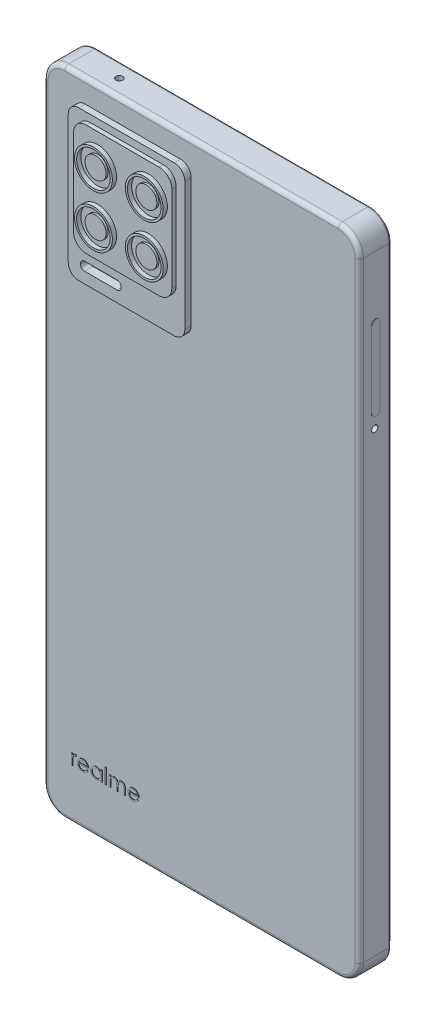
SolidWorks part; units mm, degrees
ref_plane "Front Plane" through (0, 0, 0) normal (0, 0, 1) x (1, 0, 0)
ref_plane "Top Plane" through (0, 0, 0) normal (0, 1, 0) x (1, 0, 0)
ref_plane "Right Plane" through (0, 0, 0) normal (1, 0, 0) x (0, 0, -1)
sketch "Sketch1" plane through (0, 0, 0) normal (0, 0, 1) x (1, 0, 0)
  line L1 (-14.1667, 62.0833) -> (50.8333, 62.0833)
  line L2 (-19.1667, 57.0833) -> (-19.1667, -87.9167)
  line L3 (-14.1667, -92.9167) -> (50.8333, -92.9167)
  line L4 (55.8333, 57.0833) -> (55.8333, -87.9167)
  arc A0 (50.8333, -92.9167) -> (55.8333, -87.9167) centre (50.8333, -87.9167) ccw
  arc A1 (-19.1667, -87.9167) -> (-14.1667, -92.9167) centre (-14.1667, -87.9167) ccw
  arc A2 (50.8333, 62.0833) -> (55.8333, 57.0833) centre (50.8333, 57.0833) cw
  arc A3 (-14.1667, 62.0833) -> (-19.1667, 57.0833) centre (-14.1667, 57.0833) ccw
  point P6 (55.8333, -92.9167)
  point P11 (55.8333, 62.0833)
  point P14 (-19.1667, 62.0833)
  dimension "D3" = 5
  dimension "D1" = 155
  dimension "D2" = 75
extrude "Boss-Extrude1" add sketch "Sketch1" along normal blind 7.5
sketch "Sketch2" plane through (0, 0, 7.5) normal (0, 0, 1) x (1, 0, 0)
  line L0 (-19.1667, 57.0833) -> (-19.1667, -87.9167) construction
  line L1 (-9.3422, 56.6833) -> (13.3578, 56.6833)
  line L2 (-11.8422, 54.1833) -> (-11.8422, 23.5833)
  line L3 (-9.3422, 21.0833) -> (13.3578, 21.0833)
  line L4 (15.8578, 54.1833) -> (15.8578, 23.5833)
  line L5 (50.8333, 62.0833) -> (-14.1667, 62.0833) construction
  arc A0 (-11.8422, 23.5833) -> (-9.3422, 21.0833) centre (-9.3422, 23.5833) ccw
  arc A1 (13.3578, 21.0833) -> (15.8578, 23.5833) centre (13.3578, 23.5833) ccw
  arc A2 (13.3578, 56.6833) -> (15.8578, 54.1833) centre (13.3578, 54.1833) cw
  arc A3 (-9.3422, 56.6833) -> (-11.8422, 54.1833) centre (-9.3422, 54.1833) ccw
  point P10 (-11.8422, 21.0833)
  point P13 (15.8578, 21.0833)
  point P16 (15.8578, 56.6833)
  dimension "D5" = 2.5
  dimension "D1" = 35.6
  dimension "D2" = 27.7
  dimension "D3" = 7.3244
  dimension "D4" = 5.4
extrude "Boss-Extrude3" add sketch "Sketch2" along normal blind 1.5
sketch "Sketch3" plane through (0, 0, 9) normal (0, 0, 1) x (1, 0, 0)
  line L9 (-6.5755, 55.0045) -> (10.7743, 55.0045)
  line L10 (-9.5755, 52.0045) -> (-9.5755, 31.5359)
  line L11 (-6.5755, 28.5359) -> (10.7743, 28.5359)
  line L12 (13.7743, 52.0045) -> (13.7743, 31.5359)
  arc A4 (-9.3422, 56.6833) -> (-11.8422, 54.1833) centre (-9.3422, 54.1833) ccw construction
  arc A6 (-9.5755, 31.5359) -> (-6.5755, 28.5359) centre (-6.5755, 31.5359) ccw
  arc A7 (10.7743, 28.5359) -> (13.7743, 31.5359) centre (10.7743, 31.5359) ccw
  arc A8 (10.7743, 55.0045) -> (13.7743, 52.0045) centre (10.7743, 52.0045) cw
  arc A9 (-6.5755, 55.0045) -> (-9.5755, 52.0045) centre (-6.5755, 52.0045) ccw
  dimension "D2" = 3
extrude "Boss-Extrude5" add sketch "Sketch3" along normal blind 1
sketch "Sketch4" plane through (0, 0, 9) normal (0, 0, 1) x (1, 0, 0)
  line L0 (-11.8422, 54.1833) -> (-11.8422, 23.5833) construction
  line L1 (-7.9422, 25.7817) -> (-0.2429, 25.7817)
  line L2 (-8.9422, 24.7817) -> (-8.9422, 24.7214)
  line L3 (-7.9422, 23.7214) -> (-0.2429, 23.7214)
  line L4 (0.7571, 24.7817) -> (0.7571, 24.7214)
  arc A0 (-0.2429, 25.7817) -> (0.7571, 24.7817) centre (-0.2429, 24.7817) cw
  arc A1 (-0.2429, 23.7214) -> (0.7571, 24.7214) centre (-0.2429, 24.7214) ccw
  arc A2 (-8.9422, 24.7214) -> (-7.9422, 23.7214) centre (-7.9422, 24.7214) ccw
  arc A3 (-7.9422, 25.7817) -> (-8.9422, 24.7817) centre (-7.9422, 24.7817) ccw
  dimension "D1" = 1
  dimension "D2" = 2.9
extrude "Cut-Extrude4" cut sketch "Sketch4" against normal blind 2
fillet "Fillet4" radius 1 8 edges at (-17.7022, 60.6189, 7.5) (18.3333, 62.0833, 7.5) (54.3689, 60.6189, 7.5) (55.8333, -15.4167, 7.5) (54.3689, -91.4522, 7.5) (18.3333, -92.9167, 7.5) (-17.7022, -91.4522, 7.5) (-19.1667, -15.4167, 7.5)
fillet "Fillet5" radius 0.5 8 edges at (-17.7022, 60.6189, 0) (18.3333, 62.0833, 0) (54.3689, 60.6189, 0) (55.8333, -15.4167, 0) (54.3689, -91.4522, 0) (18.3333, -92.9167, 0) (-17.7022, -91.4522, 0) (-19.1667, -15.4167, 0)
sketch "Sketch5" plane through (0, 0, 10) normal (0, 0, 1) x (1, 0, 0)
  line L0 (-3.8519, 47.8394) -> (-3.8519, 35.5813) construction
  line L1 (-3.8519, 35.5813) -> (8.2215, 35.5813) construction
  line L2 (8.2215, 35.5813) -> (8.2215, 47.8394) construction
  line L3 (8.2215, 47.8394) -> (-3.8519, 47.8394) construction
  circle A0 centre (-3.8519, 47.8394) radius 4.5
  circle A1 centre (-3.8519, 35.5813) radius 4.5
  circle A2 centre (8.2215, 35.5813) radius 4.5
  circle A3 centre (8.2215, 47.8394) radius 4.5
  circle A4 centre (-3.8519, 47.8394) radius 4
  circle A5 centre (-3.8519, 35.5813) radius 4
  circle A6 centre (8.2215, 35.5813) radius 4
  circle A7 centre (8.2215, 47.8394) radius 4
extrude "Boss-Extrude7" add sketch "Sketch5" along normal blind 1
sketch "Sketch6" plane through (0, 0, 10) normal (0, 0, 1) x (1, 0, 0)
  line L0 (-3.8519, 47.8394) -> (-3.8519, 35.5813) construction
  line L1 (-3.8519, 35.5813) -> (8.2215, 35.5813) construction
  line L2 (8.2215, 35.5813) -> (8.2215, 47.8394) construction
  line L3 (8.2215, 47.8394) -> (-3.8519, 47.8394) construction
  circle A0 centre (-3.8519, 47.8394) radius 2.5
  circle A1 centre (-3.8519, 35.5813) radius 2.5
  circle A2 centre (8.2215, 35.5813) radius 2.5
  circle A3 centre (8.2215, 47.8394) radius 2.5
extrude "Boss-Extrude8" add sketch "Sketch6" along normal blind 0.5
sketch "Sketch7" plane through (0, 0, 0) normal (0, 0, -1) x (-1, 0, 0)
  line L0 (14.1667, 61.5833) -> (-50.8333, 61.5833) construction
  line L1 (-50.8333, 60.5833) -> (14.1667, 60.5833)
  line L2 (-54.8333, 56.5833) -> (-54.8333, -87.4167)
  line L3 (-50.8333, -91.4167) -> (14.1667, -91.4167)
  line L4 (18.1667, 56.5833) -> (18.1667, -87.4167)
  line L5 (-55.3333, 57.0833) -> (-55.3333, -87.9167) construction
  arc A0 (-54.8333, -87.4167) -> (-50.8333, -91.4167) centre (-50.8333, -87.4167) ccw
  arc A1 (14.1667, -91.4167) -> (18.1667, -87.4167) centre (14.1667, -87.4167) ccw
  arc A2 (14.1667, 60.5833) -> (18.1667, 56.5833) centre (14.1667, 56.5833) cw
  arc A3 (-50.8333, 60.5833) -> (-54.8333, 56.5833) centre (-50.8333, 56.5833) ccw
  point P10 (-54.8333, -91.4167)
  point P13 (18.1667, -91.4167)
  point P18 (-54.8333, 60.5833)
  dimension "D5" = 4
  dimension "D1" = 152
  dimension "D2" = 73
  dimension "D3" = 1
  dimension "D4" = 0.5
extrude "Boss-Extrude10" add sketch "Sketch7" along normal blind 0.75
sketch "Sketch8" plane through (0, 0, -0.75) normal (0, 0, -1) x (-1, 0, 0)
  line L0 (-54.8333, 56.5833) -> (-54.8333, -87.4167) construction
  circle A0 centre (-50.0833, 55.6189) radius 2.5
  dimension "D1" = 4.75
extrude "Cut-Extrude5" cut sketch "Sketch8" against normal blind 1
sketch "Sketch9" plane through (0, 0, 0.25) normal (0, 0, -1) x (-1, 0, 0)
  circle A0 centre (-50.0833, 55.6189) radius 1.8
extrude "Boss-Extrude11" add sketch "Sketch9" along normal blind 0.5
sketch "Sketch10" plane through (-19.1667, 0, 0) normal (-1, 0, 0) x (0, 0, 1)
  line L0 (3.6793, 20.0833) -> (3.6793, 0.0833) construction
  line L1 (4.8966, 20.0833) -> (4.8966, 0.0833)
  line L2 (2.4619, 20.0833) -> (2.4619, 0.0833)
  line L3 (6.5, 62.0833) -> (0.5, 62.0833) construction
  line L4 (3.6793, -8.1676) -> (3.6793, -19.1676) construction
  line L5 (5.0214, -8.1676) -> (5.0214, -19.1676)
  line L6 (2.3372, -8.1676) -> (2.3372, -19.1676)
  arc A0 (4.8966, 20.0833) -> (2.4619, 20.0833) centre (3.6793, 20.0833) ccw
  arc A1 (2.4619, 0.0833) -> (4.8966, 0.0833) centre (3.6793, 0.0833) ccw
  arc A2 (5.0214, -8.1676) -> (2.3372, -8.1676) centre (3.6793, -8.1676) ccw
  arc A3 (2.3372, -19.1676) -> (5.0214, -19.1676) centre (3.6793, -19.1676) ccw
  point P2 (3.6793, 10.0833)
  point P7 (3.6793, -13.6676)
  dimension "D1" = 20
  dimension "D2" = 52
  dimension "D3" = 11
extrude "Boss-Extrude16" add sketch "Sketch10" along normal blind 0.75
sketch "Sketch12" plane through (0, 62.0833, 0) normal (0, 1, 0) x (1, 0, 0)
  circle A0 centre (-5.1897, -3.5) radius 0.8
extrude "Cut-Extrude7" cut sketch "Sketch12" against normal blind 8
sketch "Sketch13" plane through (0, -92.9167, 0) normal (0, -1, 0) x (1, 0, 0)
  line L0 (15.3333, 3.3594) -> (24.3333, 3.3594) construction
  line L1 (15.3333, 4.7969) -> (24.3333, 4.7969)
  line L2 (15.3333, 1.9219) -> (24.3333, 1.9219)
  line L3 (-19.1667, 6.5) -> (-19.1667, 0.5) construction
  arc A0 (15.3333, 4.7969) -> (15.3333, 1.9219) centre (15.3333, 3.3594) ccw
  arc A1 (24.3333, 1.9219) -> (24.3333, 4.7969) centre (24.3333, 3.3594) ccw
  point P2 (19.8333, 3.3594)
  dimension "D1" = 9
  dimension "D2" = 39
extrude "Cut-Extrude8" cut sketch "Sketch13" against normal blind 8
sketch "Sketch15" plane through (0, -84.9167, 0) normal (0, -1, 0) x (-1, 0, 0)
  line L1 (-15.8704, -3.1918) -> (-23.79, -3.1918)
  line L2 (-15.8704, -3.1918) -> (-15.8704, -2.9235)
  line L3 (-15.8704, -2.9235) -> (-23.79, -2.9235)
  line L4 (-23.79, -3.1918) -> (-23.79, -2.9235)
extrude "Boss-Extrude19" add sketch "Sketch15" along normal blind 7
sketch "Sketch16" plane through (0, -92.9167, 0) normal (0, -1, 0) x (-1, 0, 0)
  circle A0 centre (-45.8992, -3.3056) radius 2
extrude "Cut-Extrude9" cut sketch "Sketch16" against normal blind 7
sketch "Sketch17" plane through (0, -92.9167, 0) normal (0, -1, 0) x (1, 0, 0)
  circle A0 centre (-11.27, 3.5338) radius 1
  circle A1 centre (-8.27, 3.5338) radius 1
  circle A2 centre (-5.27, 3.5338) radius 1
  circle A3 centre (-2.27, 3.5338) radius 1
  circle A4 centre (0.73, 3.5338) radius 1
  circle A5 centre (31.8545, 3.5338) radius 1
  circle A6 centre (34.8545, 3.5338) radius 1
  dimension "D1" = 2
  dimension "D2" = 3
  dimension "D3" = 3
  dimension "D4" = 3
  dimension "D5" = 3
  dimension "D6" = 3
extrude "Cut-Extrude10" cut sketch "Sketch17" against normal blind 7
sketch "Sketch18" plane through (0, 0, -0.75) normal (0, 0, -1) x (-1, 0, 0)
  line L0 (-27.8333, 60.5833) -> (-9.8333, 60.5833) construction
  line L1 (14.1667, 60.5833) -> (-50.8333, 60.5833) construction
  line L2 (-27.8333, 62.5833) -> (-9.8333, 62.5833)
  line L3 (-27.8333, 58.5833) -> (-9.8333, 58.5833)
  line L4 (-55.3333, 57.0833) -> (-55.3333, -87.9167) construction
  arc A0 (-27.8333, 62.5833) -> (-27.8333, 58.5833) centre (-27.8333, 60.5833) ccw
  arc A1 (-9.8333, 58.5833) -> (-9.8333, 62.5833) centre (-9.8333, 60.5833) ccw
  point P4 (-18.8333, 60.5833)
  point P11 (-29.8333, 60.5833)
  dimension "D1" = 18
  dimension "D2" = 36.5
  dimension "D3" = 20
extrude "Cut-Extrude13" cut sketch "Sketch18" against normal blind 0.1
sketch "Sketch19" plane through (0, 0, -0.65) normal (0, 0, -1) x (-1, 0, 0)
  line L1 (-27.652, 59.5651) -> (-9.4358, 59.5651)
  line L2 (-27.752, 59.4651) -> (-27.752, 59.2691)
  line L3 (-27.652, 59.1691) -> (-9.4358, 59.1691)
  line L4 (-9.3358, 59.4651) -> (-9.3358, 59.2691)
  arc A0 (-9.4358, 59.5651) -> (-9.3358, 59.4651) centre (-9.4358, 59.4651) cw
  arc A1 (-9.4358, 59.1691) -> (-9.3358, 59.2691) centre (-9.4358, 59.2691) ccw
  arc A2 (-27.752, 59.2691) -> (-27.652, 59.1691) centre (-27.652, 59.2691) ccw
  arc A3 (-27.652, 59.5651) -> (-27.752, 59.4651) centre (-27.652, 59.4651) ccw
  point P7 (-9.3358, 59.5651)
  point P14 (-27.752, 59.5651)
  dimension "D2" = 0.1
  dimension "D1" = 18.4163
extrude "Boss-Extrude20" add sketch "Sketch19" along normal blind 0.1
sketch "Sketch20" plane through (0, 0, 7.5) normal (0, 0, 1) x (1, 0, 0)
  text T0 "realme\r\n"
extrude "Boss-Extrude21" add sketch "Sketch20" along normal blind 0.1
sketch "Sketch21" plane through (55.8333, 0, 0) normal (1, 0, 0) x (0, 0, -1)
  line L0 (-3.5908, 42.0833) -> (-3.5908, 24.0833) construction
  line L1 (-3.5908, 42.0833) -> (-3.5908, 24.0833) construction
  line L2 (-2.5813, 42.0833) -> (-2.5813, 24.0833)
  line L3 (-4.6003, 42.0833) -> (-4.6003, 24.0833)
  line L4 (-6.5, 57.0833) -> (-0.5, 57.0833) construction
  arc A0 (-2.5813, 42.0833) -> (-4.6003, 42.0833) centre (-3.5908, 42.0833) ccw
  arc A1 (-4.6003, 24.0833) -> (-2.5813, 24.0833) centre (-3.5908, 24.0833) ccw
  point P2 (-3.5908, 33.0833)
  point P7 (0, 0)
  point P10 (0, 0)
  dimension "D1" = 18
  dimension "D2" = 24
extrude "Boss-Extrude23" add sketch "Sketch21" along normal blind 0.05
sketch "Sketch22" plane through (55.8333, 0, 0) normal (1, 0, 0) x (0, 0, -1)
  circle A0 centre (-3.8306, 20.605) radius 0.75
  dimension "D1" = 1.5
extrude "Cut-Extrude15" cut sketch "Sketch22" against normal blind 7
